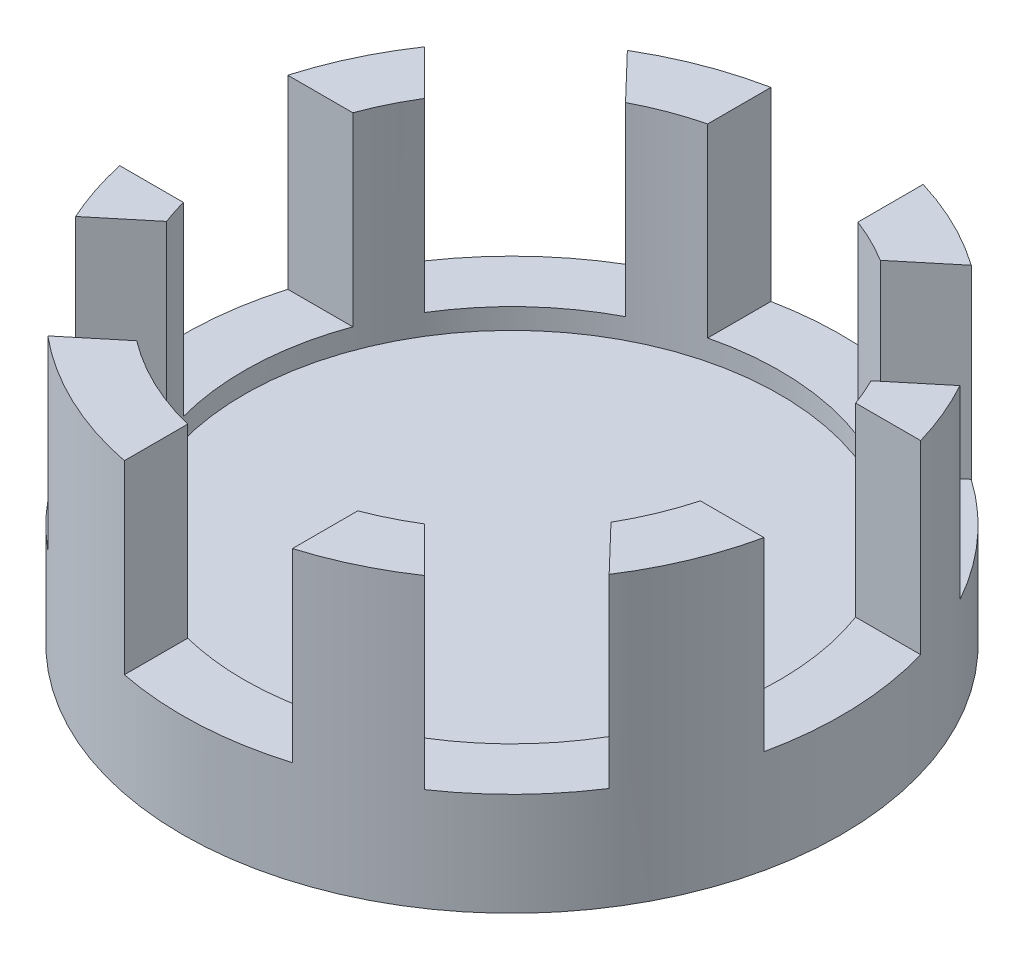
SolidWorks part; units mm, degrees
material "山毛榉"
ref_plane "前视基准面" through (0, 0, 0) normal (0, 0, 1) x (1, 0, 0)
ref_plane "上视基准面" through (0, 0, 0) normal (0, 1, 0) x (1, 0, 0)
ref_plane "右视基准面" through (0, 0, 0) normal (1, 0, 0) x (0, 0, -1)
sketch "草图1" plane through (0, 0, 0) normal (0, 1, 0) x (1, 0, 0)
  circle A0 centre (0, 0) radius 16
extrude "凸台-拉伸1" add sketch "草图1" along normal blind 20
sketch "草图2" plane through (0, 20, 0) normal (0, 1, 0) x (1, 0, 0)
  circle A0 centre (0, 0) radius 13
extrude "切除-拉伸1" cut sketch "草图2" against normal blind 16
sketch3d "3D草图1"
  line L1 (-21.1155, 20, -4.4784) -> (22.1074, 20, -4.4784)
  line L2 (-21.1155, 20, -4.4784) -> (-21.1155, 20, 3.402)
  line L3 (-21.1155, 20, 3.402) -> (22.1074, 20, 3.402)
  line L4 (22.1074, 20, -4.4784) -> (22.1074, 20, 3.402)
extrude "切除-拉伸8" cut sketch "3D草图1" along a picked direction on the side of the normal blind 15 contours L2 L3 L4 L1
sketch "草图7" plane through (0, 20, 0) normal (0, 1, 0) x (1, 0, 0)
  line L1 (4.6516, 21.8941) -> (-3.1218, 21.8941)
  line L2 (4.6516, 21.8941) -> (4.6516, -22.2542)
  line L3 (4.6516, -22.2542) -> (-3.1218, -22.2542)
  line L4 (-3.1218, 21.8941) -> (-3.1218, -22.2542)
extrude "切除-拉伸9" cut sketch "草图7" against normal blind 15
sketch "草图8" plane through (0, 20, 0) normal (0, 1, 0) x (1, 0, 0)
  line L0 (-17.4715, 13.225) -> (13.3463, -17.5929)
  line L1 (-12.6183, 18.4017) -> (19.0084, -14.5192)
  line L2 (-20.2217, -11.2837) -> (14.4787, 17.4311)
  line L3 (20.6261, 13.225) -> (-18.7742, -19.379)
  line L4 (-17.4715, 13.225) -> (-12.6183, 18.4017)
  line L5 (14.4787, 17.4311) -> (20.6261, 13.225)
  line L6 (19.0084, -14.5192) -> (13.3463, -17.5929)
  line L7 (-18.7742, -19.379) -> (-20.2217, -11.2837)
  arc M2 (4.6516, 12.1393) -> (12.2042, 4.4784) centre (0, 0) cw
  arc M4 (15.3605, 4.4784) -> (4.6516, 15.3089) centre (0, 0) ccw
extrude "切除-拉伸12" cut sketch "草图8" against normal blind 15 contours L7 L3 L0 L2 | L4 L0 L2 L1 | L3 L2 M4 M2 | L6 L1 L3 L0
sketch3d "3D草图2"
  line L1 (17.9931, 20, -18.2347) -> (-19.8852, 20, -18.2347)
  line L2 (17.9931, 20, -18.2347) -> (17.9931, 20, 17.2321)
  line L3 (17.9931, 20, 17.2321) -> (-19.8852, 20, 17.2321)
  line L4 (-19.8852, 20, -18.2347) -> (-19.8852, 20, 17.2321)
extrude "切除-拉伸14" cut sketch "3D草图2" along a picked direction on the side of the normal blind 6
